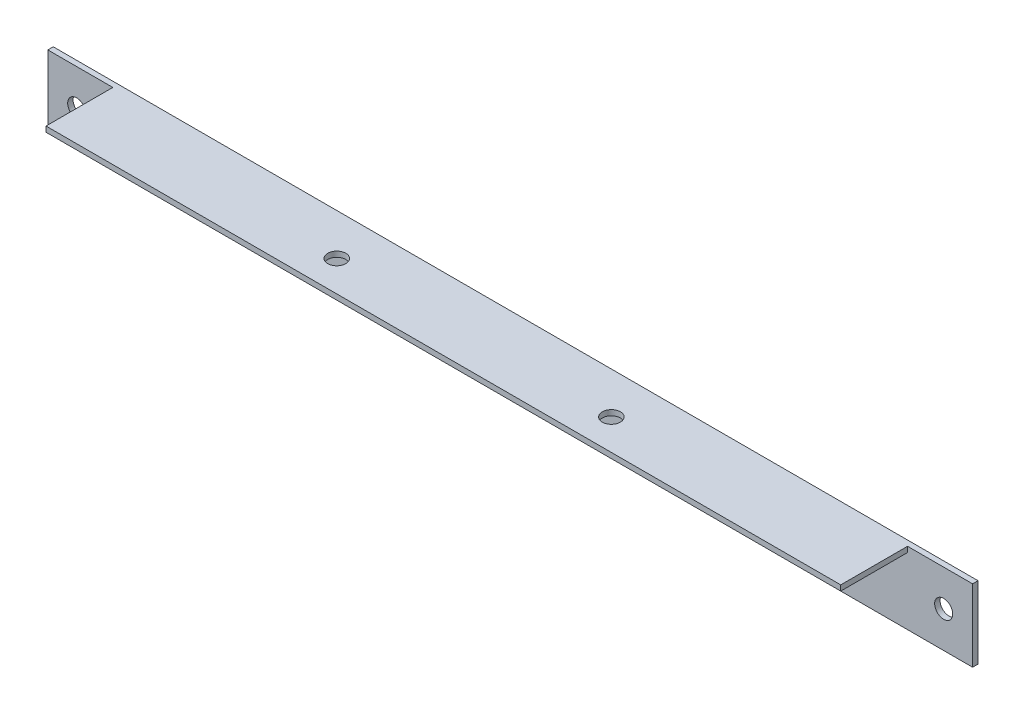
SolidWorks part; units mm, degrees
material "3.0205 (EN-AW 1200)"
ref_plane "Plan de face" through (0, 0, 0) normal (0, 0, 1) x (1, 0, 0)
ref_plane "Plan de dessus" through (0, 0, 0) normal (0, 1, 0) x (1, 0, 0)
ref_plane "Plan de droite" through (0, 0, 0) normal (1, 0, 0) x (0, 0, -1)
sketch "Esquisse1" plane through (0, 0, 0) normal (1, 0, 0) x (0, 0, -1)
  line L0 (-20, 0) -> (0, 0)
  line L1 (0, 0) -> (0, -20)
  dimension "D1" = 20
  dimension "D2" = 20
extrude "Extru.-Mince1" add sketch "Esquisse1" along normal mid plane 256 thin
sketch "Esquisse2" plane through (0, 0, 1.5) normal (0, 0, 1) x (1, 0, 0)
  line L0 (0, -20) -> (0, -1.5) construction
  line L1 (128, -20) -> (-128, -20) construction
  line L2 (128, -1.5) -> (-128, -1.5) construction
  circle A0 centre (-120, -10) radius 2.5
  circle A1 centre (120, -10) radius 2.5
  dimension "D1" = 240
  dimension "D2" = 10
  dimension "D3" = 5
extrude "Enlèv. mat.-Extru.1" cut sketch "Esquisse2" against normal blind 10
sketch "Esquisse3" plane through (0, -1.5, 0) normal (0, -1, 0) x (1, 0, 0)
  line L0 (128, 1.5) -> (-128, 1.5) construction
  line L1 (-128, 20) -> (-110, 20)
  line L2 (-128, 20) -> (-128, 1.5)
  line L3 (-128, 1.5) -> (-110, 1.5)
  line L4 (-110, 20) -> (-110, 1.5)
  line L5 (0, 0) -> (0, 20) construction
  line L6 (128, 20) -> (-128, 20) construction
  line L7 (110, 20) -> (110, 1.5)
  line L8 (128, 1.5) -> (110, 1.5)
  line L9 (128, 20) -> (128, 1.5)
  line L10 (128, 20) -> (110, 20)
  circle A0 centre (-38, 11.5) radius 2.5
  circle A1 centre (38, 11.5) radius 2.5
  dimension "D2" = 76
  dimension "D3" = 10
  dimension "D4" = 5
  dimension "D1" = 220
extrude "Enlèv. mat.-Extru.2" cut sketch "Esquisse3" against normal blind 10
